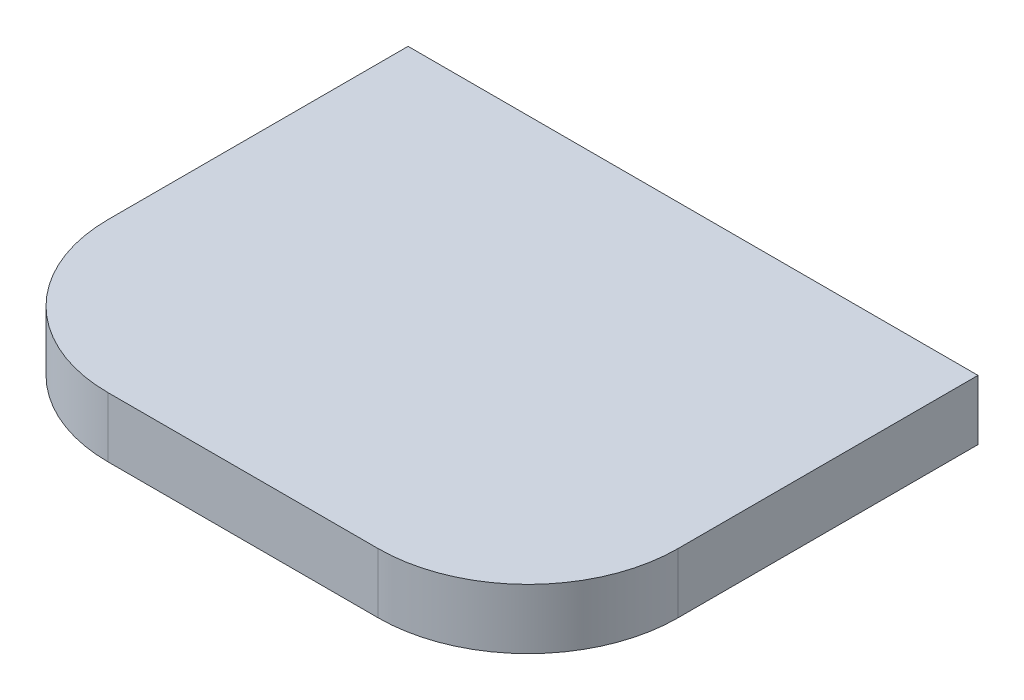
SolidWorks part; units mm, degrees
ref_plane "Alzado" through (0, 0, 0) normal (0, 0, 1) x (1, 0, 0)
ref_plane "Planta" through (0, 0, 0) normal (0, 1, 0) x (1, 0, 0)
ref_plane "Vista lateral" through (0, 0, 0) normal (1, 0, 0) x (0, 0, -1)
sketch "Croquis2" plane through (0, 0, 0) normal (0, 1, 0) x (1, 0, 0)
  line L1 (-43.1071, -17.6252) -> (-5.1071, -17.6252)
  line L2 (-43.1071, -17.6252) -> (-43.1071, -37.6252)
  line L3 (-33.1071, -47.6252) -> (-15.1071, -47.6252)
  line L4 (-5.1071, -17.6252) -> (-5.1071, -37.6252)
  arc A0 (-15.1071, -47.6252) -> (-5.1071, -37.6252) centre (-15.1071, -37.6252) ccw
  arc A1 (-33.1071, -47.6252) -> (-43.1071, -37.6252) centre (-33.1071, -37.6252) cw
  dimension "D1" = 10
extrude "Saliente-Extruir1" add sketch "Croquis2" along normal blind 4
